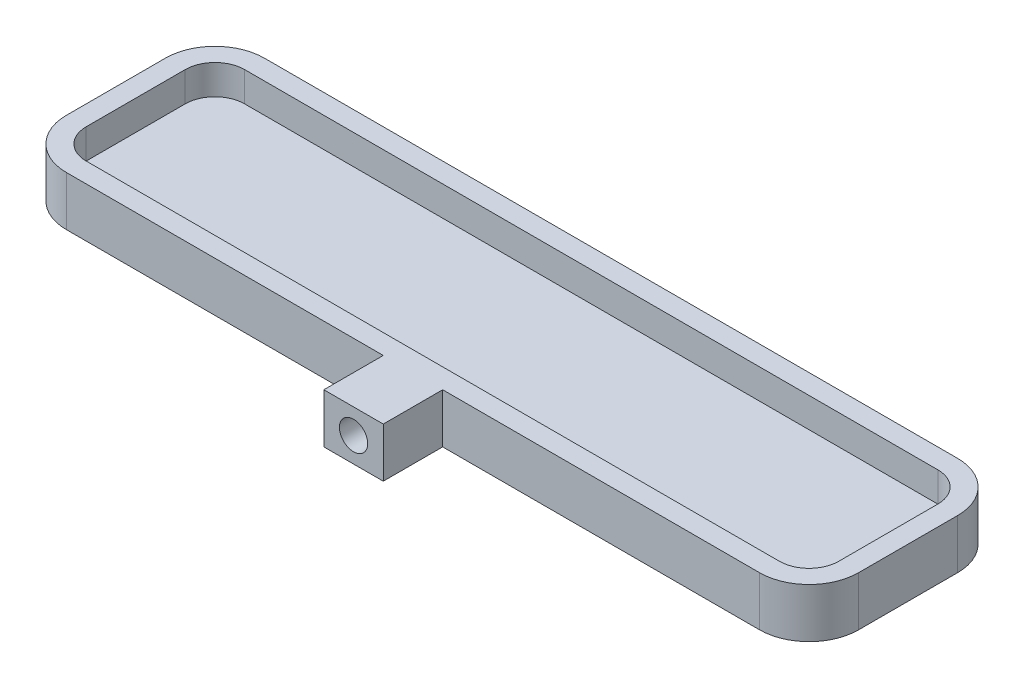
SolidWorks part; units mm, degrees
ref_plane "Front Plane" through (0, 0, 0) normal (0, 0, 1) x (1, 0, 0)
ref_plane "Top Plane" through (0, 0, 0) normal (0, 1, 0) x (1, 0, 0)
ref_plane "Right Plane" through (0, 0, 0) normal (1, 0, 0) x (0, 0, -1)
sketch "Sketch1" plane through (0, 0, 0) normal (0, 1, 0) x (1, 0, 0)
  line L1 (-40, -10) -> (40, -10)
  line L2 (-40, -10) -> (-40, 10)
  line L3 (-40, 10) -> (40, 10)
  line L4 (40, -10) -> (40, 10)
  line L5 (-40, -10) -> (40, 10) construction
  line L6 (-40, 10) -> (40, -10) construction
  point P0 (0, 0)
  dimension "D1" = 20
  dimension "D2" = 80
extrude "Boss-Extrude1" add sketch "Sketch1" along normal blind 5
fillet "Fillet1" radius 5 4 edges at (-40, 2.5, -10) (40, 2.5, -10) (40, 2.5, 10) (-40, 2.5, 10)
shell "Shell1" thickness 2
sketch "Sketch2" plane through (0, 0, 10) normal (0, 0, 1) x (1, 0, 0)
  line L2 (-3, 0) -> (-3, 5)
  line L3 (-3, 5) -> (3, 5)
  line L4 (3, 0) -> (3, 5)
  line L7 (-35, 5) -> (35, 5) construction
  line L8 (3, 0) -> (-3, 0)
  point P2 (0, 0)
  dimension "D1" = 6
extrude "Boss-Extrude2" add sketch "Sketch2" along normal blind 6
sketch "Sketch3" plane through (0, 0, 16) normal (0, 0, 1) x (1, 0, 0)
  line L0 (0, 0) -> (0, 5) construction
  line L1 (3, 5) -> (-3, 5) construction
  circle A0 centre (0, 2.5) radius 1.425
  dimension "D1" = 2.85
extrude "Cut-Extrude1" cut sketch "Sketch3" against normal blind 4
